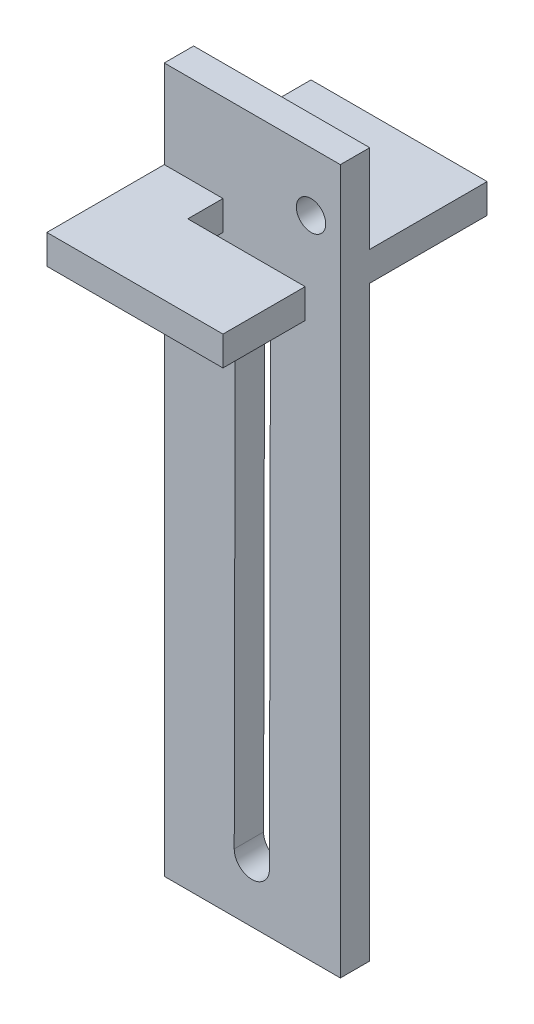
SolidWorks part; units mm, degrees
ref_plane "Front Plane" through (0, 0, 0) normal (0, 0, 1) x (1, 0, 0)
ref_plane "Top Plane" through (0, 0, 0) normal (0, 1, 0) x (1, 0, 0)
ref_plane "Right Plane" through (0, 0, 0) normal (1, 0, 0) x (0, 0, -1)
sketch "Sketch1" plane through (0, 0, 0) normal (0, 0, 1) x (1, 0, 0)
  line L0 (11.6159, 31.3531) -> (11.4483, -48.6469) construction
  line L1 (-3.4679, 41.3531) -> (26.5321, 41.3531)
  line L2 (-3.4679, 41.3531) -> (-3.4679, -58.6469)
  line L3 (-3.4679, -58.6469) -> (26.5321, -58.6469)
  line L4 (26.5321, 41.3531) -> (26.5321, -58.6469)
  line L5 (14.6159, 31.3468) -> (14.4483, -48.6532)
  line L6 (8.6159, 31.3594) -> (8.4483, -48.6406)
  arc A0 (14.6159, 31.3468) -> (8.6159, 31.3594) centre (11.6159, 31.3531) ccw
  arc A1 (8.4483, -48.6406) -> (14.4483, -48.6532) centre (11.4483, -48.6469) ccw
  point P6 (11.5321, -8.6469)
  point P11 (26.5321, -8.6469)
  point P12 (14.5321, -8.6532)
  point P14 (-3.4679, -8.6469)
  point P15 (8.5321, -8.6406)
  point P16 (11.5321, -58.6469)
  dimension "D9" = 3
  dimension "D1" = 30
  dimension "D2" = 100
  dimension "D3" = 80
  dimension "D4" = 0.12
  dimension "D5" = 12
  dimension "D6" = 12
  dimension "D7" = 10
  dimension "D8" = 10.0004
extrude "Boss-Extrude1" add sketch "Sketch1" along normal blind 5
sketch "Sketch2" plane through (0, 41.3531, 0) normal (0, 1, 0) x (1, 0, 0)
  line L0 (-3.4679, -5) -> (-3.4679, 0) construction
  line L1 (-3.4679, 20) -> (26.5321, 20)
  line L2 (-3.4679, 20) -> (-3.4679, -25)
  line L3 (-3.4679, -25) -> (26.5321, -25)
  line L4 (26.5321, 20) -> (26.5321, -25)
  line L5 (26.5321, -5) -> (26.5321, 0) construction
  line L6 (26.5321, -5) -> (-3.4679, -5) construction
  dimension "D1" = 0
  dimension "D2" = 0
  dimension "D3" = 20
  dimension "D4" = 45
extrude "Boss-Extrude2" add sketch "Sketch2" along normal blind 5
sketch "Sketch3" plane through (0, 46.3531, 0) normal (0, 1, 0) x (1, 0, 0)
  line L0 (26.5321, 20) -> (-3.4679, 20) construction
  line L1 (-3.4679, 0) -> (26.5321, 0)
  line L2 (-3.4679, 0) -> (-3.4679, -5)
  line L3 (-3.4679, -5) -> (26.5321, -5)
  line L4 (26.5321, 0) -> (26.5321, -5)
  line L5 (-3.4679, -25) -> (26.5321, -25) construction
  line L6 (-3.4679, 20) -> (-3.4679, -25) construction
  line L7 (26.5321, -25) -> (26.5321, 20) construction
  dimension "D1" = 5
  dimension "D2" = 20
  dimension "D3" = 20
  dimension "D4" = 0
  dimension "D5" = 0
extrude "Boss-Extrude3" add sketch "Sketch3" along normal blind 15
sketch "Sketch4" plane through (0, 0, 5) normal (0, 0, 1) x (1, 0, 0)
  line L0 (26.5321, 61.3531) -> (26.5321, 46.3531) construction
  line L1 (-3.4679, 46.3531) -> (26.5321, 46.3531) construction
  circle A0 centre (21.5321, 51.3531) radius 2.5
  dimension "D2" = 5
  dimension "D1" = 5
  dimension "D3" = 5
extrude "Cut-Extrude1" cut sketch "Sketch4" against normal blind 8 contours A0
sketch "Sketch5" plane through (26.5321, 0, 0) normal (1, 0, 0) x (0, 0, -1)
  line L0 (-5, 61.3531) -> (-5, 46.3531) construction
  line L1 (-11, 46.3531) -> (-5, 46.3531)
  line L2 (-11, 46.3531) -> (-11, 41.3531)
  line L3 (-11, 41.3531) -> (-5, 41.3531)
  line L4 (-5, 46.3531) -> (-5, 41.3531)
  line L5 (-25, 46.3531) -> (-5, 46.3531) construction
  line L6 (-25, 41.3531) -> (-5, 41.3531) construction
  dimension "D1" = 0
  dimension "D2" = 0
  dimension "D3" = 0
  dimension "D4" = 6
extrude "Cut-Extrude2" cut sketch "Sketch5" against normal blind 20
